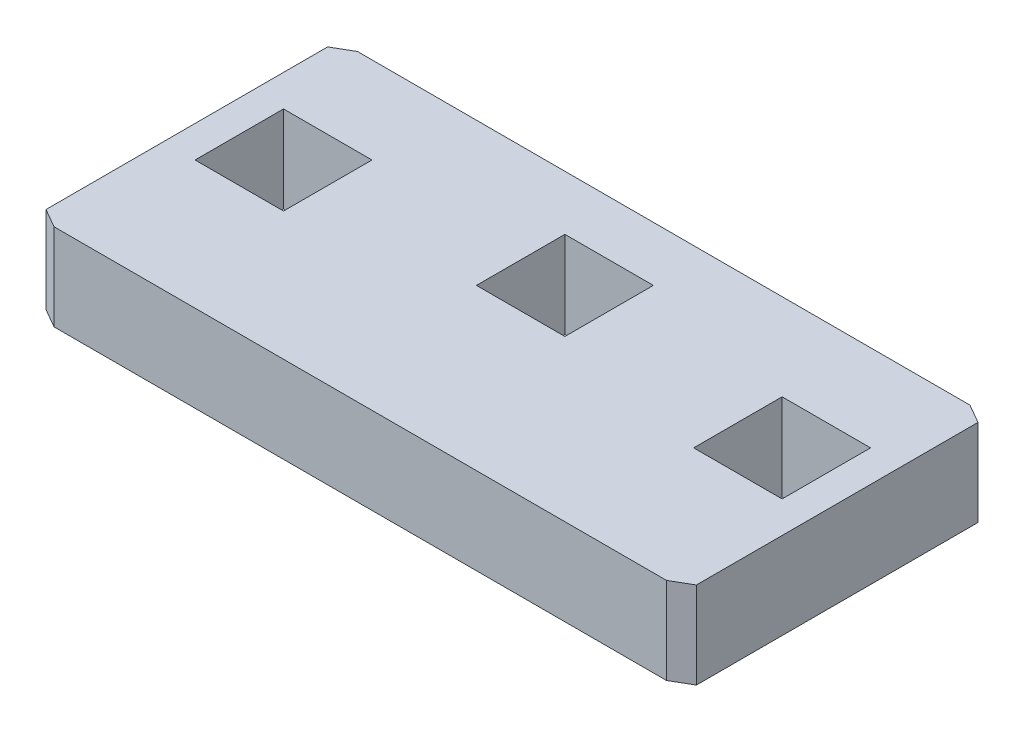
SolidWorks part; units mm, degrees
ref_plane "정면" through (0, 0, 0) normal (0, 0, 1) x (1, 0, 0)
ref_plane "윗면" through (0, 0, 0) normal (0, 1, 0) x (1, 0, 0)
ref_plane "우측면" through (0, 0, 0) normal (1, 0, 0) x (0, 0, -1)
sketch "Sketch2" plane through (0, 0, 0) normal (0, 1, 0) x (1, 0, 0)
  line L1 (-75, 35) -> (75, 35)
  line L2 (-75, 35) -> (-75, -35)
  line L3 (-75, -35) -> (75, -35)
  line L4 (75, 35) -> (75, -35)
  point P4 (0, 35)
  point P6 (-75, 0)
  dimension "D1" = 150
  dimension "D2" = 70
extrude "Extrude1" add sketch "Sketch2" along normal blind 20
sketch "Sketch3" plane through (0, 20, 0) normal (0, 1, 0) x (1, 0, 0)
  line L1 (-10.2, 22.4) -> (10.2, 22.4)
  line L2 (-10.2, 22.4) -> (-10.2, 2)
  line L3 (-10.2, 2) -> (10.2, 2)
  line L4 (10.2, 22.4) -> (10.2, 2)
  point P10 (0, 2)
  dimension "D1" = 20.4
  dimension "D2" = 20.4
  dimension "D6" = 2
extrude "Extrude2" cut sketch "Sketch3" against normal blind 20
sketch "Sketch6" plane through (0, 20, 0) normal (0, 1, 0) x (1, 0, 0)
  line L0 (-75, 35) -> (-75, -35) construction
  line L1 (-67.7, 15) -> (-47.3, 15)
  line L2 (-67.7, 15) -> (-67.7, -5.4)
  line L3 (-67.7, -5.4) -> (-47.3, -5.4)
  line L4 (-47.3, 15) -> (-47.3, -5.4)
  line L5 (0, 35) -> (0, -35) construction
  line L6 (75, 35) -> (-75, 35) construction
  line L7 (-75, -35) -> (75, -35) construction
  line L8 (67.7, -5.4) -> (47.3, -5.4)
  line L9 (47.3, 15) -> (47.3, -5.4)
  line L10 (67.7, 15) -> (47.3, 15)
  line L11 (67.7, 15) -> (67.7, -5.4)
  point P6 (-57.5, 15)
  dimension "D1" = 17.5
  dimension "D2" = 20.4
  dimension "D3" = 20.4
  dimension "D4" = 20
extrude "Extrude5" cut sketch "Sketch6" against normal blind 20
sketch "Sketch7" plane through (0, 20, 0) normal (0, 1, 0) x (1, 0, 0)
  line L0 (-70.6352, -35) -> (-75, -32.48)
  line L1 (-75, -35) -> (75, -35) construction
  line L2 (-75, 35) -> (-75, -35) construction
  line L3 (-75, -32.48) -> (-75, -35)
  line L4 (-75, -35) -> (-70.6352, -35)
  line L5 (-75, 0) -> (75, 0) construction
  line L6 (75, -35) -> (75, 35) construction
  line L7 (0, 35) -> (0, -35) construction
  line L8 (75, 35) -> (-75, 35) construction
  line L9 (-75, 35) -> (-70.6352, 35)
  line L10 (-75, 32.48) -> (-75, 35)
  line L11 (-70.6352, 35) -> (-75, 32.48)
  line L12 (75, -35) -> (70.6352, -35)
  line L13 (75, -32.48) -> (75, -35)
  line L14 (70.6352, -35) -> (75, -32.48)
  line L15 (70.6352, 35) -> (75, 32.48)
  line L16 (75, 32.48) -> (75, 35)
  line L17 (75, 35) -> (70.6352, 35)
  dimension "D1" = 30
  dimension "D2" = 5.04
extrude "Extrude6" cut sketch "Sketch7" against normal blind 20
